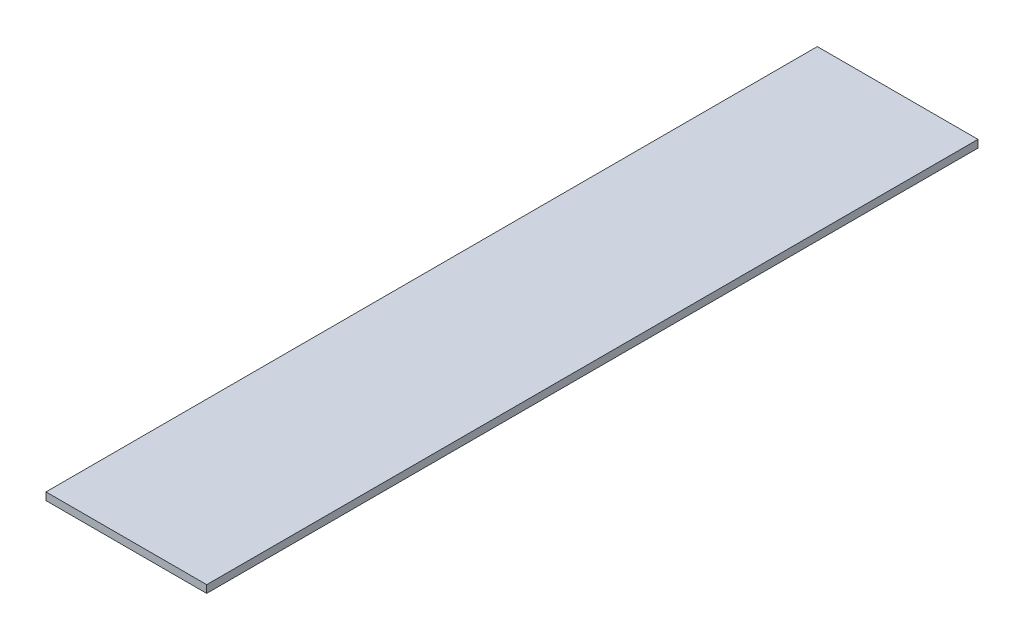
SolidWorks part; units mm, degrees
ref_plane "Front Plane" through (0, 0, 0) normal (0, 0, 1) x (1, 0, 0)
ref_plane "Top Plane" through (0, 0, 0) normal (0, 1, 0) x (1, 0, 0)
ref_plane "Right Plane" through (0, 0, 0) normal (1, 0, 0) x (0, 0, -1)
sketch "Sketch2" plane through (0, 0, 0) normal (0, 1, 0) x (1, 0, 0)
  line L1 (-12.5, -60) -> (12.5, -60)
  line L2 (-12.5, -60) -> (-12.5, 60)
  line L3 (-12.5, 60) -> (12.5, 60)
  line L4 (12.5, -60) -> (12.5, 60)
  line L5 (-12.5, -60) -> (12.5, 60) construction
  line L6 (-12.5, 60) -> (12.5, -60) construction
  point P0 (0, 0)
  dimension "D1" = 25
  dimension "D2" = 120
extrude "Boss-Extrude1" add sketch "Sketch2" along normal blind 1.18
